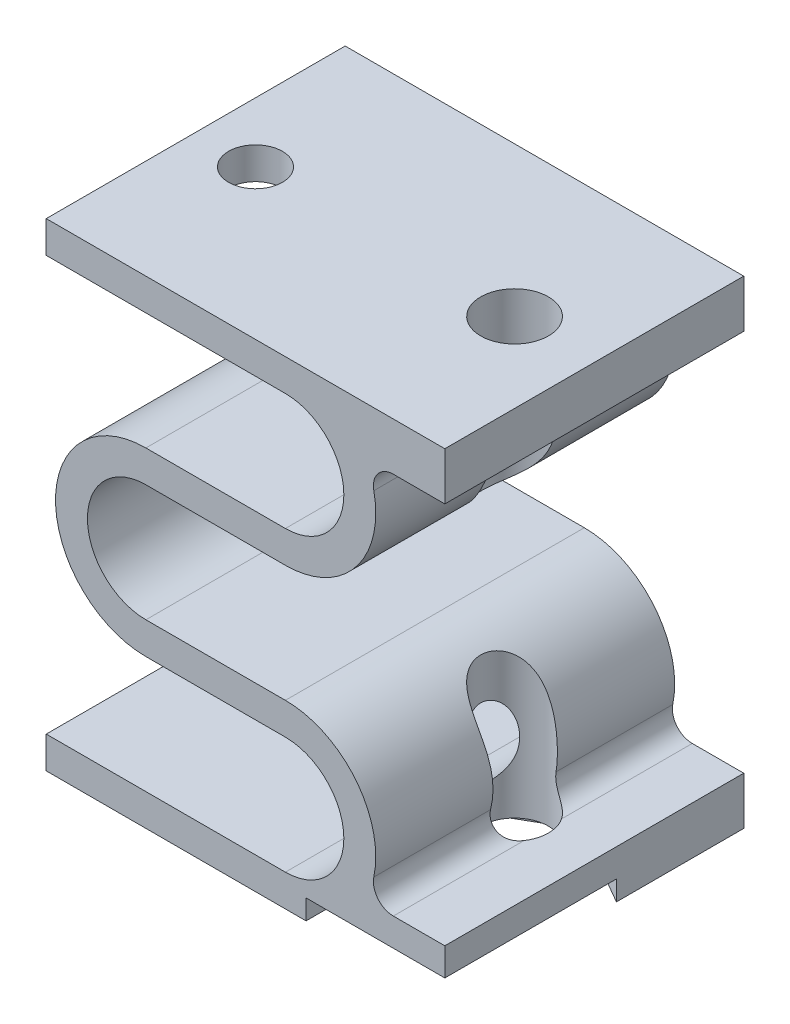
SolidWorks part; units mm, degrees
ref_plane "Front Plane" through (0, 0, 0) normal (0, 0, 1) x (1, 0, 0)
ref_plane "Top Plane" through (0, 0, 0) normal (0, 1, 0) x (1, 0, 0)
ref_plane "Right Plane" through (0, 0, 0) normal (1, 0, 0) x (0, 0, -1)
sketch "Sketch1" plane through (0, 0, 0) normal (0, 0, 1) x (1, 0, 0)
  line L0 (2.0427, 12) -> (46.3243, 12) construction
  line L1 (0, 0) -> (20, 0)
  line L2 (0, 0) -> (0, 1.6)
  line L3 (0, 1.6) -> (12, 1.6)
  line L4 (20, 0) -> (20, 2.4)
  line L5 (5, 14.9333) -> (12, 14.9333)
  line L6 (0, 22.4) -> (12, 22.4)
  line L7 (0, 24) -> (0, 22.4)
  line L8 (0, 24) -> (20, 24)
  line L9 (20, 2.4) -> (17.416, 2.4)
  line L10 (5, 9.0667) -> (12, 9.0667)
  line L11 (0, 0) -> (12, 0) construction
  line L12 (5, 7.4667) -> (12, 7.4667)
  line L13 (5, 16.5333) -> (12, 16.5333)
  line L14 (20, 24) -> (20, 21.6)
  line L15 (20, 21.6) -> (17.416, 21.6)
  line L16 (0, 24) -> (12, 24) construction
  line L17 (0, 22.4) -> (10.4, 22.4) construction
  line L18 (13.5393, 2.0364) -> (13.5393, 2.0364) construction
  line L19 (13.5393, 2.0364) -> (13.5393, 2.0364) construction
  line L20 (13.5393, 2.0364) -> (13.5393, 2.0364) construction
  line L21 (12, 22.4) -> (12, 22.4) construction
  line L22 (12, 22.4) -> (12, 22.4) construction
  line L23 (12, 22.4) -> (12, 22.4) construction
  arc A0 (16.4372, 3.6048) -> (12, 9.0667) centre (12, 4.5333) ccw
  arc A1 (12, 14.9333) -> (16.4372, 20.3952) centre (12, 19.4667) ccw
  arc A2 (5, 14.9333) -> (5, 9.0667) centre (5, 12) ccw
  arc A3 (12, 16.5333) -> (12, 22.4) centre (12, 19.4667) ccw
  arc A4 (5, 16.5333) -> (5, 7.4667) centre (5, 12) ccw
  arc A5 (12, 7.4667) -> (12, 1.6) centre (12, 4.5333) cw
  arc A6 (13.5393, 2.0364) -> (12, 7.4667) centre (12, 4.5333) ccw construction
  arc A7 (12, 16.5333) -> (12, 22.4) centre (12, 19.4667) ccw construction
  arc A8 (16.4372, 3.6048) -> (17.416, 2.4) centre (17.416, 3.4) ccw
  arc A9 (12, 0) -> (12, 9.0667) centre (12, 4.5333) ccw construction
  arc A10 (12, 14.9333) -> (12, 24) centre (12, 19.4667) ccw construction
  arc A11 (16.4372, 20.3952) -> (17.416, 21.6) centre (17.416, 20.6) cw
  dimension "D4" = 1
  dimension "D5" = 2.4
  dimension "D1" = 1
  dimension "D2" = 1.6
  dimension "D3" = 12
  dimension "D6" = 12
  dimension "D7" = 20
  dimension "D8" = 5
extrude "Boss-Extrude1" add sketch "Sketch1" along normal blind 15
sketch "Sketch2" plane through (0, 24, 0) normal (0, 1, 0) x (1, 0, 0)
  line L0 (0, -7.5) -> (46.5982, -7.5) construction
  line L1 (0, -15) -> (0, 0) construction
  circle A0 centre (16, -7.5) radius 1.7
  dimension "D1" = 3.4
  dimension "D3" = 16
extrude "Cut-Extrude1" cut sketch "Sketch2" against normal through all
sketch "Sketch3" plane through (0, 0, 0) normal (0, -1, 0) x (1, 0, 0)
  line L0 (21.1162, 7.0335) -> (21.1162, 15.482)
  line L2 (13.0379, 15.482) -> (13.0379, 5.7898)
  line L3 (13.0379, 5.7898) -> (16, 4.0797)
  line L4 (16, 4.0797) -> (21.1162, 7.0335)
  line L7 (21.1162, 15.482) -> (13.0379, 15.482)
  line L18 (18.9621, 5.7898) -> (18.9621, 9.2102) [skipped]
  line L19 (18.9621, 9.2102) -> (16, 10.9203) [skipped]
  line L20 (16, 10.9203) -> (13.0379, 9.2102) [skipped]
  circle A0 centre (16, 7.5) radius 2.9 construction
  circle A1 centre (16, 7.5) radius 1.7 construction
  dimension "D1" = 5.8
extrude "Cut-Extrude2" cut sketch "Sketch3" against normal blind 1
sketch "Sketch4" plane through (0, 24, 0) normal (0, 1, 0) x (1, 0, 0)
  line L0 (20, -7.5) -> (0, -7.5) construction
  line L1 (20, -15) -> (20, 0) construction
  line L2 (0, -15) -> (0, 0) construction
  circle A0 centre (3, -7.5) radius 1.35
  dimension "D2" = 2.7
  dimension "D1" = 3
extrude "Cut-Extrude3" cut sketch "Sketch4" against normal up to next
sketch "Sketch5" plane through (0, 0, 0) normal (0, -1, 0) x (1, 0, 0)
  circle A0 centre (3, 7.5) radius 1.35
  circle A1 centre (3, 7.5) radius 1.35 construction
extrude "Cut-Extrude4" cut sketch "Sketch5" against normal up to next
